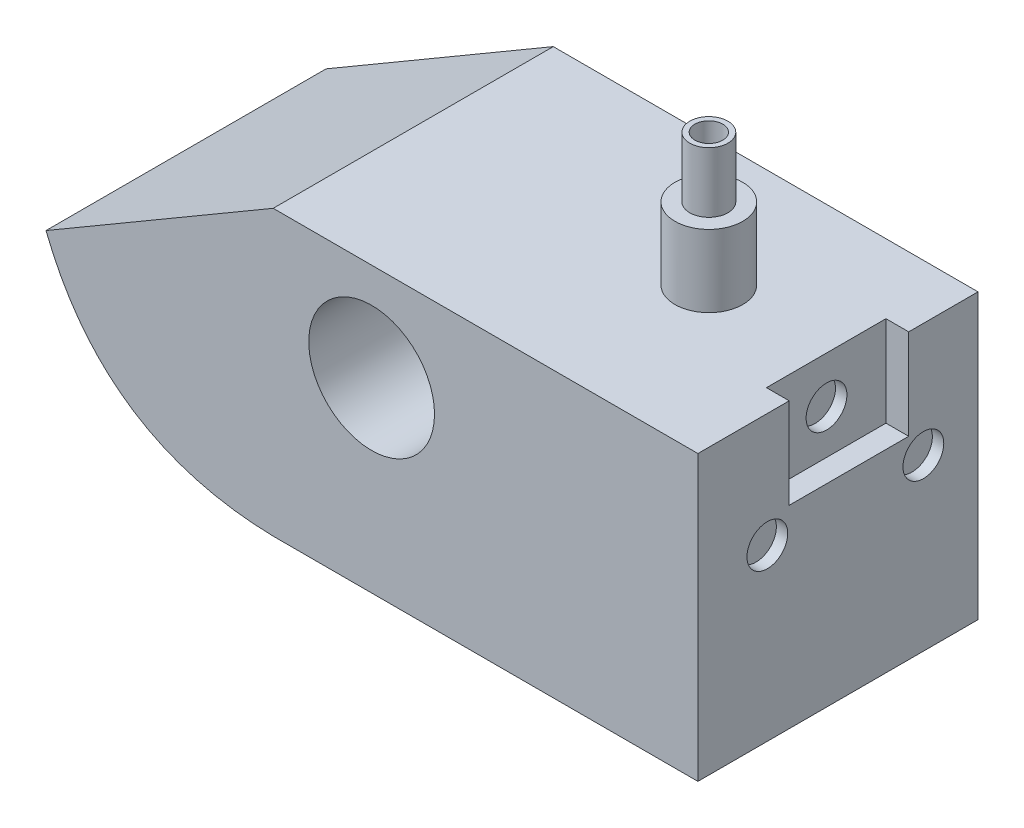
SolidWorks part; units mm, degrees
ref_plane "Front Plane" through (0, 0, 0) normal (0, 0, 1) x (1, 0, 0)
ref_plane "Top Plane" through (0, 0, 0) normal (0, 1, 0) x (1, 0, 0)
ref_plane "Right Plane" through (0, 0, 0) normal (1, 0, 0) x (0, 0, -1)
sketch "Sketch2" plane through (0, 0, 0) normal (0, 0, 1) x (1, 0, 0)
  line L1 (-73.4911, 48.7691) -> (1.1489, 48.7691)
  line L2 (-73.4911, 48.7691) -> (-73.4911, -1.1309)
  line L3 (-73.4911, -1.1309) -> (1.1489, -1.1309)
  line L4 (1.1489, 48.7691) -> (1.1489, -1.1309)
  line L5 (-73.4911, 48.7691) -> (1.1489, -1.1309) construction
  line L6 (-73.4911, -1.1309) -> (1.1489, 48.7691) construction
  circle A0 centre (-56.1911, 31.6095) radius 11.05
  point P0 (-36.1711, 23.8191)
  dimension "D4" = 17.3
  dimension "D3" = 22.1
  dimension "D1" = 49.9
  dimension "D2" = 74.64
extrude "Boss-Extrude3" add sketch "Sketch2" along normal blind 49.22
sketch "Sketch3" plane through (0, 0, 0) normal (0, 0, 1) x (1, 0, 0)
  line L0 (-73.4911, 48.7691) -> (-113.416, 25.4226)
  line L5 (1.1489, -1.1309) -> (1.1489, 48.7691)
  line L6 (1.1489, 48.7691) -> (-73.4911, 48.7691)
  line L7 (-73.4911, 48.7691) -> (-73.4911, -1.1309)
  line L8 (-73.4911, -1.1309) -> (1.1489, -1.1309)
  line L11 (-73.4911, 48.7691) -> (-73.4911, -1.1309)
  spline S0 degree 2 poles (-73.4911, -1.1309) (-103.2207, -0.4636) (-113.416, 25.4226) knots 0 0 0 1 1 1
  point P7 (-113.416, 25.4226)
  dimension "D2" = 0
  dimension "D1" = 46.25
sketch "Sketch4" plane through (0, 0, 0) normal (0, 0, 1) x (1, 0, 0)
  line L0 (-73.4911, 48.7691) -> (-73.4911, -1.1309)
  point P4 (0, 0)
extrude "Boss-Extrude4" add sketch "Sketch3" along normal blind 49.22
sketch "Sketch7" plane through (0, 48.7691, 0) normal (0, 1, 0) x (1, 0, 0)
  circle A0 centre (-23.5311, -22.62) radius 5.95
  dimension "D1" = 11.9
  dimension "D2" = 26.6
  dimension "D3" = 24.68
extrude "Boss-Extrude5" add sketch "Sketch7" along normal blind 12.67
sketch "Sketch8" plane through (0, 61.4391, 0) normal (0, 1, 0) x (1, 0, 0)
  circle A0 centre (-23.5311, -22.62) radius 3.35
  dimension "D1" = 6.7
extrude "Boss-Extrude6" add sketch "Sketch8" along normal blind 10.6
sketch "Sketch9" plane through (0, 72.0391, 0) normal (0, 1, 0) x (1, 0, 0)
  circle A0 centre (-23.5311, -22.62) radius 2.4472
extrude "Cut-Extrude1" cut sketch "Sketch9" against normal blind 4
sketch "Sketch10" plane through (1.1489, 0, 0) normal (1, 0, 0) x (0, 0, -1)
  line L0 (-33.1763, 48.7691) -> (-33.1763, 32.8691)
  line L1 (-49.22, 48.7691) -> (0, 48.7691) construction
  line L2 (-33.1763, 32.8691) -> (-12.1763, 32.8691)
  line L3 (-12.1763, 32.8691) -> (-12.1763, 48.7691)
  dimension "D1" = 21
  dimension "D2" = 15.9
extrude "Cut-Extrude2" cut sketch "Sketch10" against normal blind 4 and the other way through all
sketch "Sketch11" plane through (-2.8511, 0, 0) normal (1, 0, 0) x (0, 0, -1)
  circle A0 centre (-22.6241, 40.6278) radius 3.585
  dimension "D1" = 7.17
extrude "Cut-Extrude3" cut sketch "Sketch11" against normal blind 2
sketch "Sketch12" plane through (1.1489, 0, 0) normal (1, 0, 0) x (0, 0, -1)
  circle A0 centre (-9.6, 28.7191) radius 3.585
  dimension "D2" = 7.17
  dimension "D1" = 20.05
  dimension "D3" = 9.6
extrude "Cut-Extrude4" cut sketch "Sketch12" against normal blind 2
sketch "Sketch13" plane through (1.1489, 0, 0) normal (1, 0, 0) x (0, 0, -1)
  circle A0 centre (-37.02, 28.7191) radius 3.585
  dimension "D2" = 7.17
  dimension "D1" = 20.05
  dimension "D3" = 12.2
extrude "Cut-Extrude5" cut sketch "Sketch13" against normal blind 2
